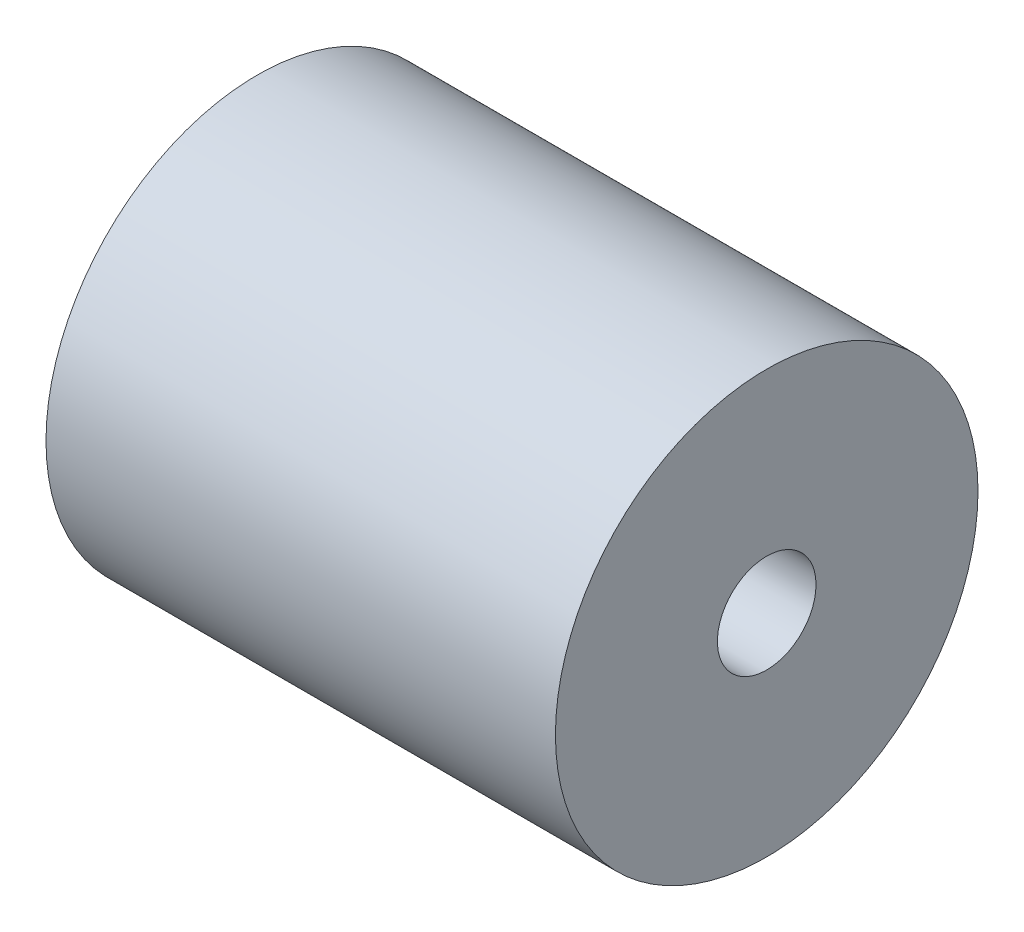
SolidWorks part; units mm, degrees
ref_plane "Front Plane" through (0, 0, 0) normal (0, 0, 1) x (1, 0, 0)
ref_plane "Top Plane" through (0, 0, 0) normal (0, 1, 0) x (1, 0, 0)
ref_plane "Right Plane" through (0, 0, 0) normal (1, 0, 0) x (0, 0, -1)
sketch "Sketch1" plane through (0, 0, 0) normal (1, 0, 0) x (0, 0, -1)
  circle A0 centre (0, 0) radius 2.1
  circle A1 centre (0, 0) radius 9
  dimension "D1" = 4.2
  dimension "D2" = 18
extrude "Boss-Extrude1" add sketch "Sketch1" along normal blind 21.7
